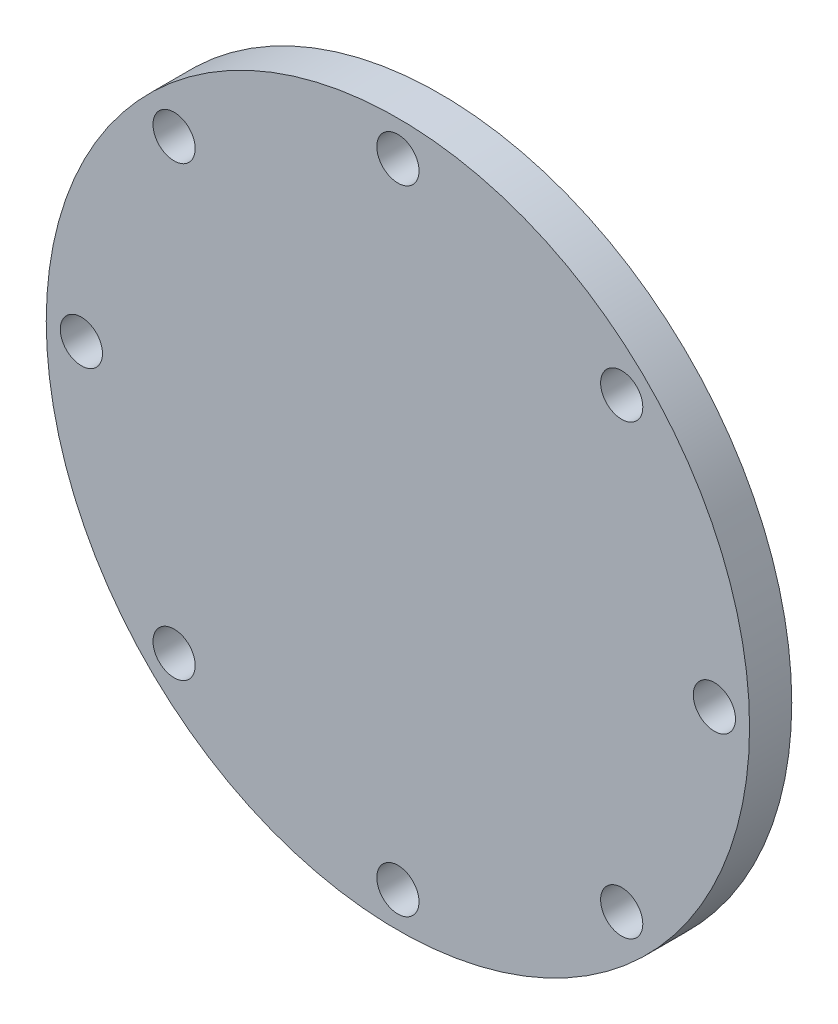
SolidWorks part; units mm, degrees
material "Glass"
ref_plane "Front Plane" through (0, 0, 0) normal (0, 0, 1) x (1, 0, 0)
ref_plane "Top Plane" through (0, 0, 0) normal (0, 1, 0) x (1, 0, 0)
ref_plane "Right Plane" through (0, 0, 0) normal (1, 0, 0) x (0, 0, -1)
sketch "Sketch1" plane through (0, 0, 0) normal (0, 0, 1) x (1, 0, 0)
  circle A0 centre (0, 0) radius 25
  circle A2 centre (0, 0) radius 22.5 construction
  circle A3 centre (0, 22.5) radius 1.5
  circle A4 centre (15.9099, 15.9099) radius 1.5
  circle A5 centre (22.5, 0) radius 1.5
  circle A6 centre (15.9099, -15.9099) radius 1.5
  circle A7 centre (0, -22.5) radius 1.5
  circle A8 centre (-15.9099, -15.9099) radius 1.5
  circle A9 centre (-22.5, 0) radius 1.5
  circle A10 centre (-15.9099, 15.9099) radius 1.5
  point P8 (-17.2409, 17.6816)
  point P9 (0, 0)
  point P23 (0, 0)
  dimension "D1" = 50
  dimension "D3" = 45
  dimension "D4" = 3
  dimension "D5" = 8
extrude "Boss-Extrude1" add sketch "Sketch1" along normal blind 3
